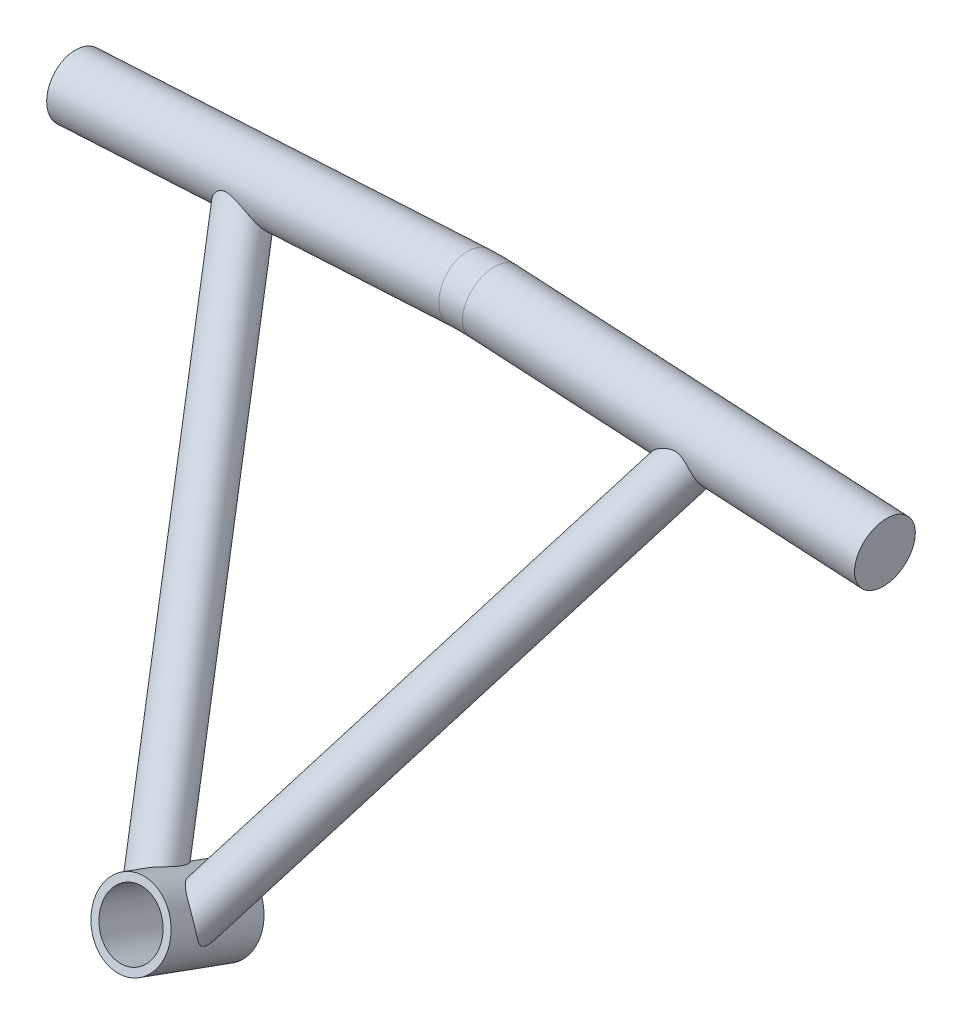
SolidWorks part; units mm, degrees
material "AISI 4130 Steel, normalized at 870C"
ref_plane "Front Plane" through (0, 0, 0) normal (0, 0, 1) x (1, 0, 0)
ref_plane "Top Plane" through (0, 0, 0) normal (0, 1, 0) x (1, 0, 0)
ref_plane "Right Plane" through (0, 0, 0) normal (1, 0, 0) x (0, 0, -1)
sketch "Sketch3" plane through (0, 0, 0) normal (0, 1, 0) x (1, 0, 0)
  line L0 (-5.08, -6.35) -> (5.08, -6.35) construction
  line L2 (0, -88.2205) -> (0, 88.2205) construction
  line L3 (5.08, 0) -> (-5.08, 0) construction
  dimension "D1" = 5.08
  dimension "D2" = 10.16
  dimension "D3" = 6.35
  dimension "D4" = 10.16
  dimension "D5" = 5.08
ref_plane "Plane1" through (0, 3.1268, 3.7263) normal (0, 0.6428, 0.766) x (1, 0, 0)
ref_plane "Plane3" through (0, 0, 0) normal (0, 0.342, 0.9397) x (-1, 0, 0)
sketch "Sketch1" plane through (0, 0, 0) normal (0, 0.342, 0.9397) x (1, 0, 0)
  circle A0 centre (0, 0) radius 15.875
  dimension "D1" = 31.75
extrude "Boss-Extrude1" add sketch "Sketch1" along normal mid plane 41.402 contours A0
sketch "Sketch4" plane through (0, 3.1268, 3.7263) normal (0, 0.6428, 0.766) x (1, 0, 0)
  line L0 (-5.08, -4.0817) -> (-96.7686, 201.8543)
  line L2 (0, -24.1976) -> (0, 24.1976) construction
  dimension "D2" = 24
  dimension "D3" = 225.425
sweep "Sweep1" add path "Sketch4" circular profile diameter 19.05 parameters "D3"=19.05
sketch "Sketch15" plane through (0, 3.1268, 3.7263) normal (0, 0.6428, 0.766) x (1, 0, 0)
  line L0 (5.08, -4.0817) -> (96.7686, 201.8543)
  line L1 (0, -87.2383) -> (0, 87.2383) construction
  dimension "D1" = 225.425
  dimension "D2" = 24
sweep "Sweep2" add path "Sketch15" circular profile diameter 19.05 parameters "D3"=19.05
sketch "Sketch2" plane through (0, -7.0802, -19.4526) normal (0, -0.342, -0.9397) x (-1, 0, 0)
  circle A0 centre (0, 0) radius 12.7
  dimension "D1" = 25.4
extrude "Cut-Extrude1" cut sketch "Sketch2" against normal up to next
sketch "Sketch36" plane through (-91.0124, 156.5926, -131.3968) normal (-0.4067, 0.6998, -0.5872) x (0.9135, 0.3116, -0.2614)
  circle A0 centre (-6.301, -4.8644) radius 7.9375
  dimension "D1" = 15.875
extrude "Cut-Extrude2" cut sketch "Sketch36" against normal blind 127
sketch "Sketch37" plane through (91.0124, 156.5926, -131.3968) normal (0.4067, 0.6998, -0.5872) x (0.9135, -0.3116, 0.2614)
  circle A0 centre (6.301, -4.8644) radius 7.9375
  dimension "D1" = 15.875
extrude "Cut-Extrude3" cut sketch "Sketch37" against normal blind 127
ref_plane "Plane2" through (0, 0, -127) normal (0, 0, 1) x (1, 0, 0)
sketch "Sketch40" plane through (-106.934, 0, -127) normal (0, 0, 1) x (1, 0, 0)
  line L2 (106.934, -87.2383) -> (106.934, 87.2383) construction
  line L3 (101.9947, 162.4227) -> (-62.0894, 153.292)
  line L4 (111.8733, 162.4227) -> (275.9574, 153.292)
  arc A0 (101.9947, 162.4227) -> (111.8733, 162.4227) centre (106.934, 73.66) cw
  point P0 (106.934, 162.56)
  point P4 (0, 0)
  point P7 (106.934, 162.56)
  point P9 (0, 0)
  point P11 (0, 0)
  point P12 (0, 0)
  dimension "D1" = 164.338
  dimension "D3" = 88.9
  dimension "D2" = 164.338
  dimension "D4" = 9.8786
sweep "Sweep3" add path "Sketch40" circular profile diameter 25.4 parameters "D3"=25.4
